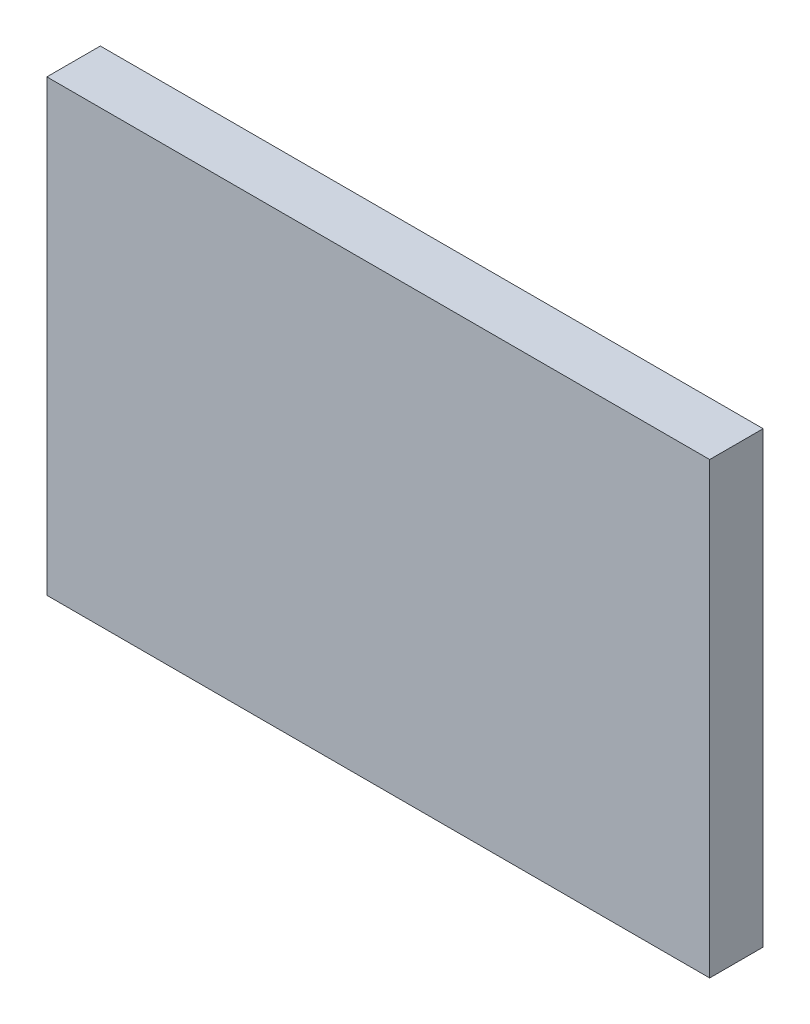
SolidWorks part; units mm, degrees
ref_plane "Front Plane" through (0, 0, 0) normal (0, 0, 1) x (1, 0, 0)
ref_plane "Top Plane" through (0, 0, 0) normal (0, 1, 0) x (1, 0, 0)
ref_plane "Right Plane" through (0, 0, 0) normal (1, 0, 0) x (0, 0, -1)
sketch "Sketch1" plane through (0, 0, 0) normal (0, 0, 1) x (1, 0, 0)
  line L0 (0, -25) -> (0, -21) construction
  line L1 (31, 21) -> (-31, 21)
  line L2 (31, 21) -> (31, -21)
  line L3 (31, -21) -> (-31, -21)
  line L4 (-31, 21) -> (-31, -21)
  line L5 (31, 21) -> (-31, -21) construction
  line L6 (31, -21) -> (-31, 21) construction
  line L8 (31, 0) -> (35, 0) construction
  point P0 (0, 0)
  point P14 (0, 0)
  dimension "D1" = 4
extrude "Boss-Extrude1" add sketch "Sketch1" along normal blind 5
